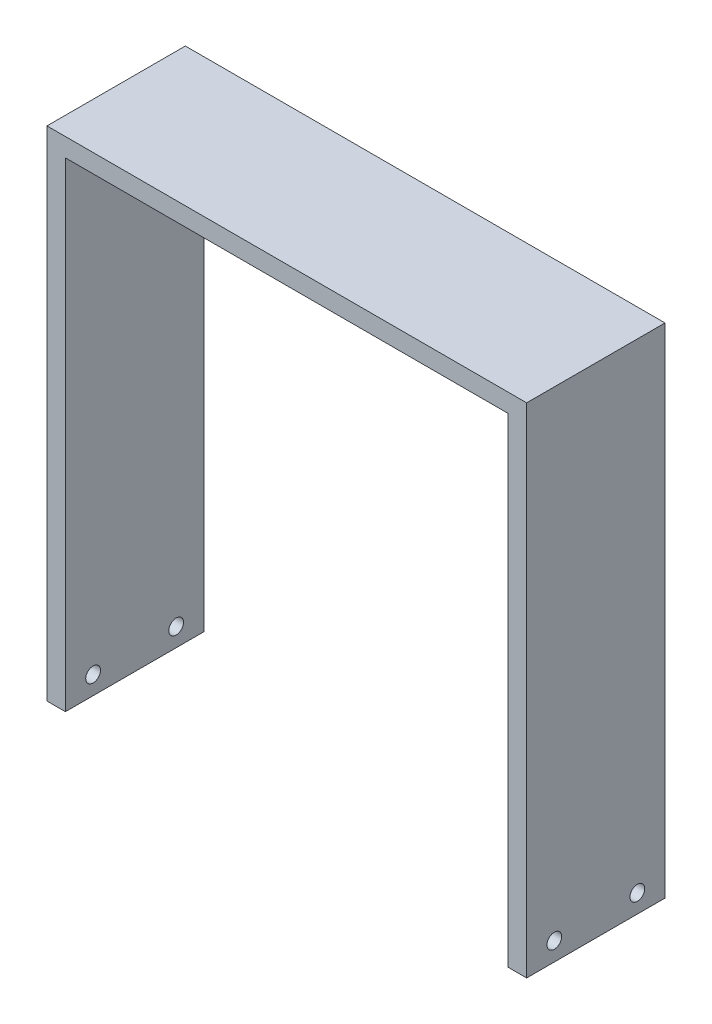
SolidWorks part; units mm, degrees
material "1060 Alloy"
ref_plane "Front Plane" through (0, 0, 0) normal (0, 0, 1) x (1, 0, 0)
ref_plane "Top Plane" through (0, 0, 0) normal (0, 1, 0) x (1, 0, 0)
ref_plane "Right Plane" through (0, 0, 0) normal (1, 0, 0) x (0, 0, -1)
sketch "Sketch1" plane through (0, 0, 0) normal (0, 0, 1) x (1, 0, 0)
  line L0 (0, 0) -> (0, 54)
  line L1 (0, 54) -> (52, 54)
  line L2 (52, 54) -> (52, 0)
  line L3 (52, 0) -> (50, 0)
  line L4 (50, 0) -> (50, 52)
  line L5 (50, 52) -> (2, 52)
  line L6 (2, 52) -> (2, 0)
  line L7 (2, 0) -> (0, 0)
  dimension "D1" = 2
  dimension "D2" = 2
  dimension "D3" = 2
  dimension "D4" = 48
  dimension "D5" = 54
extrude "Boss-Extrude1" add sketch "Sketch1" along normal blind 15
sketch "Sketch2" plane through (52, 0, 0) normal (1, 0, 0) x (0, 0, -1)
  line L0 (0, 0) -> (0, 54) construction
  line L1 (-15, 0) -> (0, 0) construction
  line L2 (-15, 0) -> (-15, 54) construction
  circle A0 centre (-13, 1.5) radius 1
  circle A1 centre (-2, 1.5) radius 1
  dimension "D1" = 2
  dimension "D2" = 2
  dimension "D3" = 2
  dimension "D4" = 1.5
  dimension "D5" = 1.5
  dimension "D6" = 2
extrude "Cut-Extrude1" [suppressed] cut sketch "Sketch2" against normal up to surface (2 mm away)
hole_wizard "M2 Tapped Hole1" positions "Sketch4" profile "Sketch5" tap size "M2" standard "ISO"
sketch "Sketch4" plane through (52, 0, 0) normal (1, 0, 0) x (0, 0, -1)
  line L0 (-15, 0) -> (0, 0) construction
  line L1 (-15, 0) -> (-15, 54) construction
  point P0 (-12, 2)
  dimension "D1" = 2
  dimension "D2" = 3
sketch "Sketch5" plane through (52, 2, 12) normal (0, 1, 0) x (0, 0, -1)
  line L0 (0, 0) -> (0, 50.4797)
  line L1 (0, 50.4797) -> (0.8, 49.999)
  line L2 (0.8, 49.999) -> (0.8, 0)
  line L5 (0.8, 0) -> (0, 0)
  line L10 (0, 50.4797) -> (-0.8, 49.999) construction
  line L11 (0, -6.35) -> (0, 107.95) construction
  dimension "Tap Drill Dia." = 1.6
  dimension "Tap Drill Depth" = 49.999
  dimension "Drill Angle" = 118
cosmetic thread "Hole Thread1" parameters "D1"=2, "D2"=2
ref_plane "Plane1" through (0, 0, 7.5) normal (0, 0, 1) x (1, 0, 0)
mirror "Mirror1" about plane through (0, 0, 7.5) normal (0, 0, 1) of "M2 Tapped Hole1"
ref_plane "Plane2" through (26, 0, 0) normal (1, 0, 0) x (0, 0, -1)
mirror "Mirror2" about plane through (26, 0, 0) normal (1, 0, 0) of "Mirror1", "M2 Tapped Hole1"
equation "\"D2@Sketch2\"=\"D1@Sketch2\""
